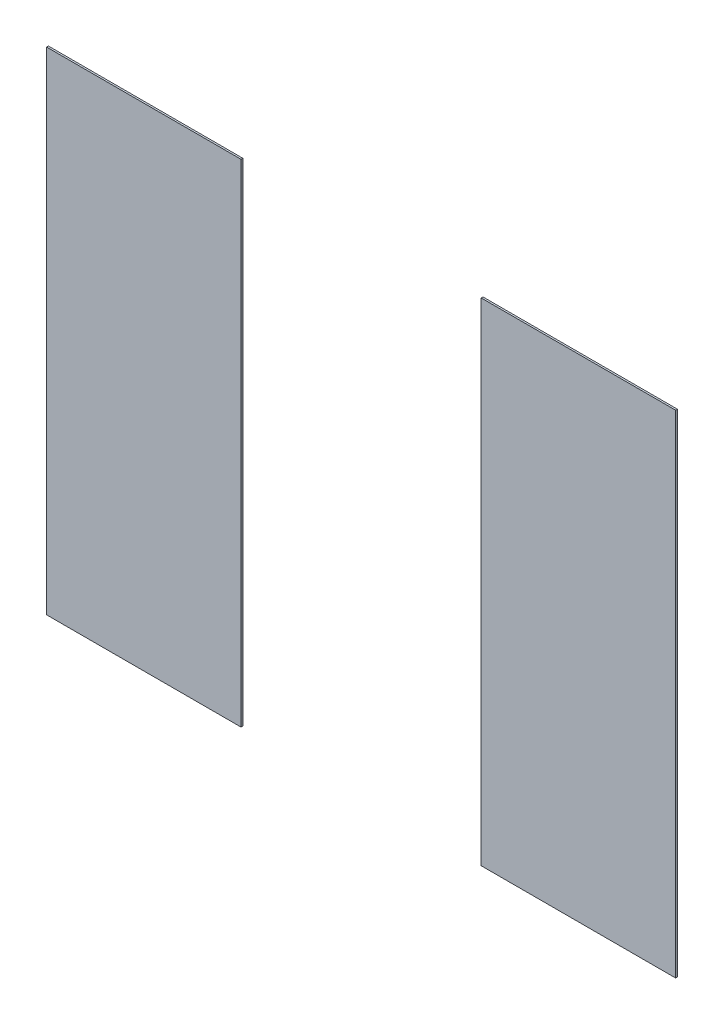
SolidWorks part; units mm, degrees
ref_plane "前视基准面" through (0, 0, 0) normal (0, 0, 1) x (1, 0, 0)
ref_plane "上视基准面" through (0, 0, 0) normal (0, 1, 0) x (1, 0, 0)
ref_plane "右视基准面" through (0, 0, 0) normal (1, 0, 0) x (0, 0, -1)
sketch "草图1" plane through (0, 0, 0) normal (0, 0, 1) x (1, 0, 0)
  line L1 (-3.4925, 2.7305) -> (-1.3335, 2.7305)
  line L2 (-3.4925, 2.7305) -> (-3.4925, -2.7305)
  line L3 (-3.4925, -2.7305) -> (-1.3335, -2.7305)
  line L4 (-1.3335, 2.7305) -> (-1.3335, -2.7305)
  line L5 (-3.4925, 2.7305) -> (-1.3335, -2.7305) construction
  line L6 (-3.4925, -2.7305) -> (-1.3335, 2.7305) construction
  line L7 (1.3335, 2.7305) -> (3.4925, 2.7305)
  line L8 (1.3335, 2.7305) -> (1.3335, -2.7305)
  line L9 (1.3335, -2.7305) -> (3.4925, -2.7305)
  line L10 (3.4925, 2.7305) -> (3.4925, -2.7305)
  line L11 (1.3335, 2.7305) -> (3.4925, -2.7305) construction
  line L12 (1.3335, -2.7305) -> (3.4925, 2.7305) construction
  point P0 (-2.413, 0)
  point P5 (2.413, 0)
  dimension "D1" = 2.7305
  dimension "D2" = 2.159
  dimension "D3" = 2.7305
  dimension "D4" = 2.159
extrude "凸台-拉伸1" add sketch "草图1" along normal blind 0.02
